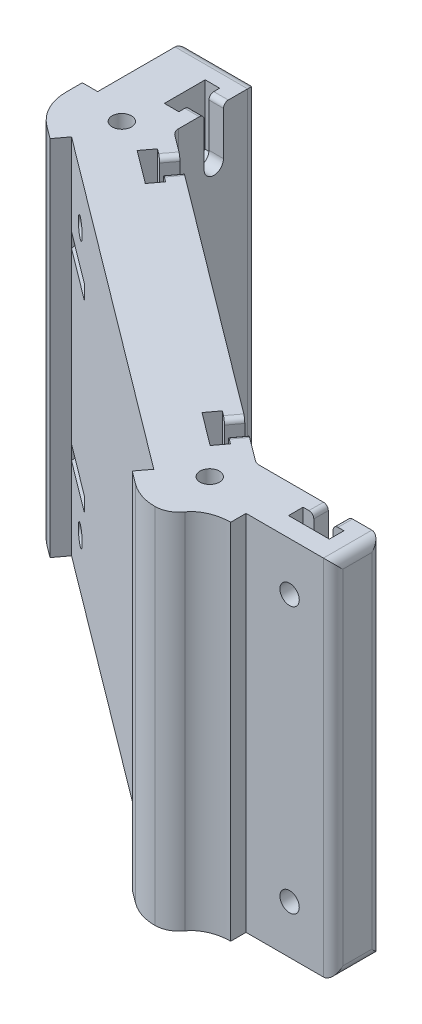
SolidWorks part; units mm, degrees
ref_plane "Front Plane" through (0, 0, 0) normal (0, 0, 1) x (1, 0, 0)
ref_plane "Top Plane" through (0, 0, 0) normal (0, 1, 0) x (1, 0, 0)
ref_plane "Right Plane" through (0, 0, 0) normal (1, 0, 0) x (0, 0, -1)
sketch "Sketch1" plane through (0, 0, 0) normal (0, 1, 0) x (1, 0, 0)
  line L0 (0, -10) -> (0, -6.825) construction
  line L2 (28.6667, -1.825) -> (28.6667, 86) construction
  line L3 (-6, -8) -> (-4.095, -5.46) construction
  line L6 (-4.095, -5.46) -> (0, 0) construction
  line L7 (0, -10) -> (-3.3333, -10) construction
  line L8 (0, 0) -> (0, -6.825) construction
  line L9 (-3.1623, -9.4868) -> (0, 0) construction
  line L10 (0, 0) -> (28.6667, 86) construction
  line L12 (-18.0283, 23.74) -> (2.725, 8.175)
  line L13 (28.6667, -1.825) -> (28.6667, 8.175)
  line L14 (28.6667, 8.175) -> (2.725, 8.175)
  line L15 (-6, -8) -> (-8.6667, -6)
  line L16 (-8.6667, -6) -> (-6.7617, -3.46)
  line L18 (10.6667, -5) -> (10.6667, -1.825)
  line L19 (-74.7617, 47.54) -> (-6.7617, -3.46)
  line L20 (-6.7617, -3.46) -> (-4.095, -5.46) construction
  line L22 (10.6667, -1.825) -> (28.6667, -1.825)
  line L23 (-6, -8) -> (-79.3333, 47) construction
  line L24 (-3.3333, -10) -> (-6, -8) construction
  line L25 (-8.6667, -6) -> (-83.3333, 50) construction
  line L26 (-74.7617, 47.54) -> (-76.6667, 45)
  line L27 (-76.6667, 45) -> (-79.3333, 47)
  line L28 (-83.3333, 50) -> (-83.3333, 76.3333) construction
  line L29 (-83.3333, 55) -> (-83.3333, 58.3333)
  line L30 (-83.3333, 58.3333) -> (-80.1583, 58.3333)
  line L31 (-80.1583, 58.3333) -> (-80.1583, 76.3333)
  line L32 (28.6667, 86) -> (-27.0283, 11.74) construction
  line L33 (-80.1583, 76.3333) -> (-65.1583, 76.3333)
  line L34 (-65.1583, 76.3333) -> (-65.1583, 59.0875)
  line L35 (-82.2776, 50.5279) -> (-65.1583, 59.0875) construction
  line L36 (-65.1583, 59.0875) -> (-51.3617, 48.74)
  line L37 (-51.3617, 48.74) -> (-60.3617, 36.74) construction
  line L38 (-51.3617, 48.74) -> (-18.0283, 23.74)
  line L39 (-83.3333, 76.3333) -> (-80.1583, 76.3333) construction
  arc A0 (0, -10) -> (-6, -8) centre (0, 0) cw
  arc A1 (-83.3333, 55) -> (-79.3333, 47) centre (-73.3333, 55) ccw
  arc A2 (0, -10) -> (4.1098, -7.8477) centre (0, -5) ccw
  ellipse E0 centre (10.6667, -10) end of major axis (3.4023, -10) minor radius 5 (4.1098, -7.8477) -> (10.6667, -5) cw
  dimension "D1" = 10
  dimension "D3" = 60
  dimension "D7" = 3.3333
  dimension "D8" = 5
  dimension "D9" = 3.175
  dimension "D2" = 15
  dimension "D4" = 18
  dimension "D5" = 10.6667
  dimension "D6" = 5
  dimension "D10" = 3.175
  dimension "D11" = 80
  dimension "D12" = 18
extrude "Boss-Extrude1" add sketch "Sketch1" along normal blind 75
sketch "Sketch2" plane through (0, 0, 1.825) normal (0, 0, 1) x (1, 0, 0)
  line L0 (19.6667, 0) -> (19.6667, 75) construction
  line L1 (10.6667, 0) -> (28.6667, 0) construction
  line L2 (10.6667, 75) -> (28.6667, 75) construction
  circle A0 centre (19.6667, 10) radius 2
  circle A1 centre (19.6667, 65) radius 2
  dimension "D1" = 4
  dimension "D2" = 10
  dimension "D3" = 10
extrude "Cut-Extrude1" cut sketch "Sketch2" against normal up to surface (10 mm away) up to face at (15.6958, 37.5, -8.175)
sketch "Sketch3" plane through (-4.095, 0, 5.46) normal (-0.6, 0, 0.8) x (0.8, 0, 0.6)
  line L0 (-12.3333, 0) -> (-12.3333, 75) construction
  line L1 (-88.3333, 0) -> (-3.3333, 0) construction
  line L2 (-88.3333, 75) -> (-3.3333, 75) construction
  line L3 (-3.3333, 75) -> (-3.3333, 0) construction
  line L4 (-45.8333, 0) -> (-45.8333, 75) construction
  line L5 (-88.3333, 0) -> (-3.3333, 0) construction
  line L6 (-88.3333, 75) -> (-3.3333, 75) construction
  circle A0 centre (-12.3333, 10) radius 2
  circle A1 centre (-12.3333, 65) radius 2
  circle A2 centre (-79.3333, 10) radius 2
  circle A3 centre (-79.3333, 65) radius 2
  dimension "D1" = 4
  dimension "D3" = 10
  dimension "D2" = 10
  dimension "D4" = 9
extrude "Cut-Extrude2" cut sketch "Sketch3" against normal up to surface (15 mm away) up to face at (-31.2167, 37.5, -33.6312)
sketch "Sketch4" plane through (-80.1583, 0, 0) normal (-1, 0, 0) x (0, 0, 1)
  line L0 (-67.3333, 0) -> (-67.3333, 75) construction
  line L1 (-76.3333, 0) -> (-58.3333, 0) construction
  line L2 (-76.3333, 75) -> (-58.3333, 75) construction
  circle A0 centre (-67.3333, 10) radius 2
  circle A1 centre (-67.3333, 65) radius 2
  dimension "D1" = 4
  dimension "D2" = 10
  dimension "D3" = 10
extrude "Cut-Extrude3" cut sketch "Sketch4" against normal up to surface (15 mm away) up to face at (-65.1583, 37.5, -67.7104)
sketch "Sketch6" plane through (4.905, 0, -6.54) normal (0.6, 0, -0.8) x (-0.8, 0, -0.6)
  line L0 (8.1146, 62.5643) -> (12.3333, 60.1286)
  line L1 (12.3333, 60.1286) -> (16.5521, 62.5643) construction
  line L2 (16.5521, 62.5643) -> (16.5521, 67.4357) construction
  line L3 (16.5521, 67.4357) -> (12.3333, 69.8714) construction
  line L4 (12.3333, 69.8714) -> (8.1146, 67.4357) construction
  line L5 (8.1146, 67.4357) -> (8.1146, 62.5643) construction
  line L6 (8.1146, 62.5643) -> (12.3333, 60.1286) construction
  line L7 (12.3333, 5.1286) -> (16.5521, 7.5643) construction
  line L8 (16.5521, 7.5643) -> (16.5521, 12.4357) construction
  line L9 (16.5521, 12.4357) -> (12.3333, 14.8714) construction
  line L10 (12.3333, 14.8714) -> (8.1146, 12.4357) construction
  line L11 (8.1146, 12.4357) -> (8.1146, 7.5643) construction
  line L12 (8.1146, 7.5643) -> (12.3333, 5.1286) construction
  line L13 (79.3333, 5.1286) -> (83.5521, 7.5643) construction
  line L14 (83.5521, 7.5643) -> (83.5521, 12.4357) construction
  line L15 (83.5521, 12.4357) -> (79.3333, 14.8714) construction
  line L16 (79.3333, 14.8714) -> (75.1146, 12.4357) construction
  line L17 (75.1146, 12.4357) -> (75.1146, 7.5643) construction
  line L18 (75.1146, 7.5643) -> (79.3333, 5.1286) construction
  line L19 (79.3333, 60.1286) -> (83.5521, 62.5643) construction
  line L20 (83.5521, 62.5643) -> (83.5521, 67.4357) construction
  line L21 (83.5521, 67.4357) -> (79.3333, 69.8714) construction
  line L22 (79.3333, 69.8714) -> (75.1146, 67.4357) construction
  line L23 (75.1146, 67.4357) -> (75.1146, 62.5643) construction
  line L24 (75.1146, 62.5643) -> (79.3333, 60.1286) construction
  line L25 (12.3333, 60.1286) -> (16.5521, 62.5643)
  line L26 (16.5521, 62.5643) -> (16.5521, 75)
  line L27 (2.725, 75) -> (87.5792, 75) construction
  line L28 (16.5521, 75) -> (8.1146, 75)
  line L29 (8.1146, 75) -> (8.1146, 62.5643)
  line L30 (75.1146, 62.5643) -> (79.3333, 60.1286)
  line L31 (79.3333, 60.1286) -> (83.5521, 62.5643)
  line L32 (83.5521, 62.5643) -> (83.5521, 75)
  line L33 (83.5521, 75) -> (75.1146, 75)
  line L34 (75.1146, 75) -> (75.1146, 62.5643)
  line L35 (8.1146, 12.4357) -> (12.3333, 14.8714)
  line L36 (12.3333, 14.8714) -> (16.5521, 12.4357)
  line L37 (16.5521, 12.4357) -> (16.5521, 0)
  line L38 (2.725, 0) -> (87.5792, 0) construction
  line L39 (16.5521, 0) -> (8.1146, 0)
  line L40 (8.1146, 0) -> (8.1146, 12.4357)
  line L41 (75.1146, 12.4357) -> (79.3333, 14.8714)
  line L42 (79.3333, 14.8714) -> (83.5521, 12.4357)
  line L43 (83.5521, 12.4357) -> (83.5521, 0)
  line L44 (83.5521, 0) -> (75.1146, 0)
  line L45 (75.1146, 0) -> (75.1146, 12.4357)
  circle A0 centre (12.3333, 65) radius 4.2187 construction
  circle A1 centre (12.3333, 10) radius 4.2188 construction
  circle A2 centre (79.3333, 10) radius 4.2187 construction
  circle A3 centre (79.3333, 65) radius 4.2187 construction
  dimension "D1" = 8.4375
extrude "Cut-Extrude5" cut sketch "Sketch6" against normal blind 3 from offset 3 offset against normal yes
sketch "Sketch7" plane through (4.905, 0, -6.54) normal (0.6, 0, -0.8) x (-0.8, 0, -0.6)
  line L0 (14.3333, 65) -> (14.3333, 75)
  line L1 (2.725, 75) -> (87.5792, 75) construction
  line L2 (14.3333, 75) -> (10.3333, 75)
  line L3 (10.3333, 75) -> (10.3333, 65)
  line L4 (81.3333, 65) -> (81.3333, 75)
  line L5 (81.3333, 0) -> (77.3333, 0)
  line L6 (2.725, 37.5) -> (87.5792, 37.5) construction
  line L7 (2.725, 75) -> (2.725, 0) construction
  line L8 (87.5792, 75) -> (87.5792, 0) construction
  line L18 (81.3333, 75) -> (77.3333, 75)
  line L19 (77.3333, 75) -> (77.3333, 65)
  line L20 (81.3333, 10) -> (81.3333, 0)
  line L21 (77.3333, 0) -> (77.3333, 10)
  line L22 (14.3333, 0) -> (10.3333, 0)
  line L23 (14.3333, 10) -> (14.3333, 0)
  line L24 (10.3333, 0) -> (10.3333, 10)
  arc A0 (10.3333, 65) -> (14.3333, 65) centre (12.3333, 65) cw
  circle A1 centre (12.3333, 65) radius 2 construction
  arc A5 (77.3333, 65) -> (81.3333, 65) centre (79.3333, 65) cw
  circle A6 centre (79.3333, 65) radius 2 construction
  arc A7 (77.3333, 10) -> (81.3333, 10) centre (79.3333, 10) ccw
  arc A8 (10.3333, 10) -> (14.3333, 10) centre (12.3333, 10) ccw
extrude "Cut-Extrude6" cut sketch "Sketch7" against normal blind 3
sketch "Sketch8" plane through (0, 0, -8.175) normal (0, 0, -1) x (-1, 0, 0)
  line L0 (-23.8854, 0) -> (-23.8854, 12.4357)
  line L1 (-19.6667, 60.1286) -> (-15.4479, 62.5643) construction
  line L2 (-15.4479, 62.5643) -> (-15.4479, 67.4357) construction
  line L3 (-15.4479, 67.4357) -> (-19.6667, 69.8714) construction
  line L4 (-19.6667, 69.8714) -> (-23.8854, 67.4357) construction
  line L5 (-23.8854, 67.4357) -> (-23.8854, 62.5643) construction
  line L6 (-23.8854, 62.5643) -> (-19.6667, 60.1286) construction
  line L7 (-19.6667, 5.1286) -> (-15.4479, 7.5643) construction
  line L8 (-15.4479, 7.5643) -> (-15.4479, 12.4357) construction
  line L9 (-15.4479, 12.4357) -> (-19.6667, 14.8714) construction
  line L10 (-19.6667, 14.8714) -> (-23.8854, 12.4357) construction
  line L11 (-23.8854, 12.4357) -> (-23.8854, 7.5643) construction
  line L12 (-23.8854, 7.5643) -> (-19.6667, 5.1286) construction
  line L13 (-28.6667, 0) -> (-2.725, 0) construction
  line L14 (-23.8854, 12.4357) -> (-19.6667, 14.8714)
  line L15 (-19.6667, 14.8714) -> (-15.4479, 12.4357)
  line L16 (-15.4479, 12.4357) -> (-15.4479, 0)
  line L17 (-15.4479, 0) -> (-23.8854, 0)
  line L18 (-23.8854, 62.5643) -> (-19.6667, 60.1286)
  line L19 (-19.6667, 60.1286) -> (-15.4479, 62.5643)
  line L20 (-15.4479, 62.5643) -> (-15.4479, 75)
  line L21 (-28.6667, 75) -> (-2.725, 75) construction
  line L22 (-15.4479, 75) -> (-23.8854, 75)
  line L23 (-23.8854, 75) -> (-23.8854, 62.5643)
  circle A0 centre (-19.6667, 65) radius 4.2187 construction
  circle A1 centre (-19.6667, 10) radius 4.2188 construction
  dimension "D1" = 8.4375
extrude "Cut-Extrude7" cut sketch "Sketch8" against normal blind 3 from offset 3 offset against normal yes
sketch "Sketch9" plane through (0, 0, -8.175) normal (0, 0, -1) x (-1, 0, 0)
  line L0 (-17.6667, 65) -> (-17.6667, 75)
  line L1 (-28.6667, 75) -> (-2.725, 75) construction
  line L2 (-17.6667, 75) -> (-21.6667, 75)
  line L3 (-21.6667, 75) -> (-21.6667, 65)
  line L4 (-21.6667, 10) -> (-21.6667, 0)
  line L5 (-28.6667, 0) -> (-2.725, 0) construction
  line L6 (-21.6667, 0) -> (-17.6667, 0)
  line L7 (-17.6667, 0) -> (-17.6667, 10)
  arc A0 (-21.6667, 65) -> (-17.6667, 65) centre (-19.6667, 65) cw
  circle A1 centre (-19.6667, 65) radius 2 construction
  arc A2 (-21.6667, 10) -> (-17.6667, 10) centre (-19.6667, 10) ccw
  circle A3 centre (-19.6667, 10) radius 2 construction
extrude "Cut-Extrude8" cut sketch "Sketch9" against normal blind 3
sketch "Sketch10" plane through (-65.1583, 0, 0) normal (1, 0, 0) x (0, 0, -1)
  line L0 (63.1146, 62.5643) -> (67.3333, 60.1286)
  line L1 (67.3333, 60.1286) -> (71.5521, 62.5643) construction
  line L2 (71.5521, 62.5643) -> (71.5521, 67.4357) construction
  line L3 (71.5521, 67.4357) -> (67.3333, 69.8714) construction
  line L4 (67.3333, 69.8714) -> (63.1146, 67.4357) construction
  line L5 (63.1146, 67.4357) -> (63.1146, 62.5643) construction
  line L6 (63.1146, 62.5643) -> (67.3333, 60.1286) construction
  line L7 (67.3333, 5.1286) -> (71.5521, 7.5643) construction
  line L8 (71.5521, 7.5643) -> (71.5521, 12.4357) construction
  line L9 (71.5521, 12.4357) -> (67.3333, 14.8714) construction
  line L10 (67.3333, 14.8714) -> (63.1146, 12.4357) construction
  line L11 (63.1146, 12.4357) -> (63.1146, 7.5643) construction
  line L12 (63.1146, 7.5643) -> (67.3333, 5.1286) construction
  line L13 (67.3333, 60.1286) -> (71.5521, 62.5643)
  line L14 (71.5521, 62.5643) -> (71.5521, 75)
  line L15 (59.0875, 75) -> (76.3333, 75) construction
  line L16 (71.5521, 75) -> (63.1146, 75)
  line L17 (63.1146, 75) -> (63.1146, 62.5643)
  line L18 (63.1146, 12.4357) -> (67.3333, 14.8714)
  line L19 (67.3333, 14.8714) -> (71.5521, 12.4357)
  line L20 (71.5521, 12.4357) -> (71.5521, 0)
  line L21 (59.0875, 0) -> (76.3333, 0) construction
  line L22 (71.5521, 0) -> (63.1146, 0)
  line L23 (63.1146, 0) -> (63.1146, 12.4357)
  circle A0 centre (67.3333, 65) radius 4.2188 construction
  circle A1 centre (67.3333, 10) radius 4.2188 construction
  dimension "D1" = 8.4375
extrude "Cut-Extrude9" cut sketch "Sketch10" against normal blind 3 from offset 3 offset against normal yes
sketch "Sketch5" plane through (0, 75, 0) normal (0, 1, 0) x (1, 0, 0)
  line L0 (-3.1623, -9.4868) -> (2.725, 8.175) construction
  line L1 (-82.2776, 50.5279) -> (-65.1583, 59.0875) construction
  line L2 (-72.3333, 55.5) -> (0.3333, 1) construction
  line L3 (-74.7617, 47.54) -> (-6.7617, -3.46) construction
  line L4 (-8.6667, -6) -> (-6, -8) construction
  arc A0 (-6, -8) -> (0, -10) centre (0, 0) ccw construction
  arc A1 (-83.3333, 55) -> (-79.3333, 47) centre (-73.3333, 55) ccw construction
  circle A2 centre (0.3333, 1) radius 2
  circle A3 centre (-72.3333, 55.5) radius 2
  dimension "D1" = 4
  dimension "D2" = 11
extrude "Cut-Extrude4" cut sketch "Sketch5" against normal up to surface (75 mm away) contours A2 | A3 up to face at (-69.6583, 0, -67.3333)
sketch "Sketch11" plane through (-65.1583, 0, 0) normal (1, 0, 0) x (0, 0, -1)
  line L0 (69.3333, 65) -> (69.3333, 75)
  line L1 (59.0875, 75) -> (76.3333, 75) construction
  line L2 (69.3333, 75) -> (65.3333, 75)
  line L3 (65.3333, 75) -> (65.3333, 65)
  line L4 (69.3333, 10) -> (69.3333, 0)
  line L5 (59.0875, 0) -> (76.3333, 0) construction
  line L6 (69.3333, 0) -> (65.3333, 0)
  line L7 (65.3333, 0) -> (65.3333, 10)
  arc A0 (65.3333, 65) -> (69.3333, 65) centre (67.3333, 65) cw
  circle A1 centre (67.3333, 65) radius 2 construction
  arc A2 (65.3333, 10) -> (69.3333, 10) centre (67.3333, 10) ccw
  circle A3 centre (67.3333, 10) radius 2 construction
extrude "Cut-Extrude10" cut sketch "Sketch11" against normal blind 3
ref_plane "Plane1" through (0, 37.5, 0) normal (0, 1, 0) x (1, 0, 0)
fillet "Fillet1" radius 1 16 edges at (-66.6583, 75, -69.3333) (-66.6583, 75, -65.3333) (-57.8617, 75, -51.74) (-61.0617, 75, -54.14) (-66.6583, 0, -69.3333) (-66.6583, 0, -65.3333) (-61.0617, 0, -54.14) (-57.8617, 0, -51.74) (-7.4617, 0, -13.94) (-4.2617, 0, -11.54) (21.6667, 0, -6.675) (17.6667, 0, -6.675) (-7.4617, 75, -13.94) (-4.2617, 75, -11.54) (17.6667, 75, -6.675) (21.6667, 75, -6.675)
fillet "Fillet2" radius 2 10 edges at (28.6667, 75, -3.175) (-72.6583, 75, -76.3333) (-72.6583, 0, -76.3333) (28.6667, 0, -3.175) (-80.1583, 37.5, -76.3333) (-65.1583, 37.5, -76.3333) (-65.1583, 37.5, -59.0875) (2.725, 37.5, -8.175) (28.6667, 37.5, -8.175) (28.6667, 37.5, 1.825)
sketch "Sketch12" plane through (0, 75, 0) normal (0, 1, 0) x (1, 0, 0)
  line L1 (5.202, 1.1639) -> (2.6257, 5.2983)
  line L2 (2.6257, 5.2983) -> (-2.2429, 5.1344)
  line L3 (-2.2429, 5.1344) -> (-4.5353, 0.8361) construction
  line L4 (-4.5353, 0.8361) -> (-1.959, -3.2983) construction
  line L5 (-1.959, -3.2983) -> (2.9096, -3.1344)
  line L6 (2.9096, -3.1344) -> (5.202, 1.1639)
  line L13 (-75.8673, 52.1471) -> (-71.1966, 50.7631) construction
  line L14 (-71.1966, 50.7631) -> (-67.6627, 54.116) construction
  line L15 (-67.6627, 54.116) -> (-68.7994, 58.8529)
  line L16 (-68.7994, 58.8529) -> (-73.4701, 60.2369)
  line L17 (-73.4701, 60.2369) -> (-77.004, 56.884)
  line L18 (-77.004, 56.884) -> (-75.8673, 52.1471)
  line L19 (-1.959, -3.2983) -> (-6.7617, -3.46)
  line L21 (-6.7617, -3.46) -> (-17.5345, 4.6196)
  line L23 (-75.8673, 52.1471) -> (-74.7617, 47.54)
  line L24 (-76.6667, 45) -> (-74.7617, 47.54) construction
  line L26 (-74.7617, 47.54) -> (-64.1802, 39.6039)
  line L27 (-74.7617, 47.54) -> (-6.7617, -3.46) construction
  line L28 (-64.1802, 39.6039) -> (-67.6627, 54.116)
  line L29 (-17.5345, 4.6196) -> (-2.2429, 5.1344)
  circle A0 centre (0.3333, 1) radius 4.2188 construction
  circle A1 centre (-72.3333, 55.5) radius 4.2187 construction
  dimension "D1" = 8.4375
extrude "Cut-Extrude11" cut sketch "Sketch12" against normal blind 3 from offset 17 offset against normal yes
mirror "Mirror1" about plane through (0, 37.5, 0) normal (0, 1, 0) of "Cut-Extrude11"
equation "\"0.25i\"=3"
